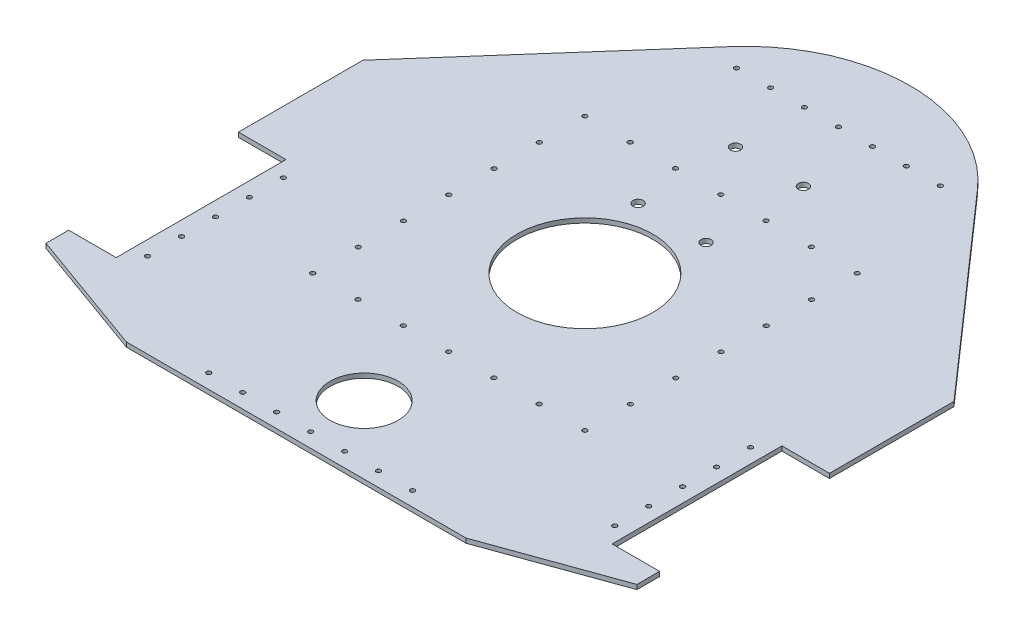
SolidWorks part; units mm, degrees
ref_plane "Front Plane" through (0, 0, 0) normal (0, 0, 1) x (1, 0, 0)
ref_plane "Top Plane" through (0, 0, 0) normal (0, 1, 0) x (1, 0, 0)
ref_plane "Right Plane" through (0, 0, 0) normal (1, 0, 0) x (0, 0, -1)
sketch "Sketch1" plane through (0, 0, 0) normal (0, 1, 0) x (1, 0, 0)
  line L0 (-240, -25) -> (240, -25) construction
  line L1 (240, -25) -> (0, 215) construction
  line L2 (0, 215) -> (-240, -25) construction
  line L3 (0, 215) -> (0, -25) construction
  line L6 (-219, 50) -> (-219, -100)
  line L7 (-219, -100) -> (-261, -100)
  line L8 (-261, -100) -> (-261, -120)
  line L10 (-150, -160) -> (150, -160)
  line L11 (-219, 50) -> (-261, 50)
  line L12 (-261, 50) -> (-261, 160)
  line L13 (-261, 160) -> (-110, 331.6587)
  line L14 (-150, -160) -> (-261, -120)
  line L15 (261, 160) -> (110, 331.6587)
  line L16 (150, -160) -> (261, -120)
  line L18 (261, -100) -> (261, -120)
  line L19 (219, -100) -> (261, -100)
  line L20 (219, 50) -> (219, -100)
  line L21 (219, 50) -> (261, 50)
  line L22 (261, 50) -> (261, 160)
  arc A7 (110, 331.6587) -> (-110, 331.6587) centre (0, 237.0979) ccw
  circle A8 centre (0, 64.773) radius 330 construction
  point P11 (-567.7272, -8.2112)
  point P29 (0, 331.6587)
  dimension "D1" = 480
  dimension "D4" = 75
  dimension "D6" = 20
  dimension "D7" = 42
  dimension "D2" = 240
  dimension "D3" = 21
  dimension "D5" = 75
  dimension "D8" = 20
  dimension "D9" = 21
  dimension "D10" = 21
  dimension "D11" = 110
  dimension "D12" = 110
  dimension "D13" = 150
  dimension "D14" = 42
  dimension "D15" = 300
extrude "Boss-Extrude1" add sketch "Sketch1" along normal blind 4
sketch "Sketch2" plane through (0, 4, 0) normal (0, 1, 0) x (1, 0, 0)
  line L0 (-206.3, 24.3269) -> (-206.3, -74.3269) construction
  line L1 (-219, 50) -> (-219, -100) construction
  line L2 (0, 319.1541) -> (0, -121.9152) construction
  line L4 (-219, 50) -> (-261, 50) construction
  line L5 (219, 50) -> (261, 50) construction
  circle A0 centre (-206.3, -25) radius 2
  circle A1 centre (-206.3, 5) radius 2
  circle A2 centre (-206.3, 35) radius 2
  circle A3 centre (-206.3, -55) radius 2
  circle A4 centre (-206.3, -85) radius 2
  circle A6 centre (206.3, -85) radius 2
  circle A7 centre (206.3, -55) radius 2
  circle A8 centre (206.3, -25) radius 2
  circle A9 centre (206.3, 5) radius 2
  circle A10 centre (206.3, 35) radius 2
  dimension "D2" = 3
  dimension "D1" = 12.7
  dimension "D4" = 75
  dimension "D5" = 75
  dimension "D6" = 12.7
  dimension "D3" = 3
extrude "Cut-Extrude1" cut sketch "Sketch2" against normal up to surface (4 mm away) up to face at (0, 0, -17.1134)
sketch "Sketch4" plane through (0, 4, 0) normal (0, 1, 0) x (1, 0, 0)
  line L0 (0, 0) -> (0, -135) construction
  line L1 (-120.2082, 215.2082) -> (-120.2082, -25.2082) construction
  line L2 (-219, -25) -> (219, -25) construction
  line L7 (-219, 50) -> (-219, -100) construction
  line L8 (219, 50) -> (219, -100) construction
  line L9 (-150, -160) -> (150, -160) construction
  line L10 (0, 382.1556) -> (0, -160) construction
  line L11 (0, 95) -> (-120.2082, 215.2082) construction
  circle A5 centre (0, -100) radius 30
  arc A6 (110, 331.6587) -> (-110, 331.6587) centre (0, 237.0979) ccw construction
  circle A7 centre (-120.2082, 215.2082) radius 2
  circle A8 centre (0, 95) radius 60
  circle A9 centre (120.2082, 215.2082) radius 2
  circle A10 centre (120.2082, -25.2082) radius 2
  circle A11 centre (-120.2082, -25.2082) radius 2
  circle A12 centre (-120.2082, 95) radius 2
  circle A13 centre (-120.2082, 135) radius 2
  circle A14 centre (-120.2082, 175) radius 2
  circle A15 centre (-120.2082, 55) radius 2
  circle A16 centre (-120.2082, 15) radius 2
  circle A17 centre (120.2082, 15) radius 2
  circle A18 centre (120.2082, 55) radius 2
  circle A19 centre (120.2082, 95) radius 2
  circle A20 centre (120.2082, 135) radius 2
  circle A21 centre (120.2082, 175) radius 2
  circle A22 centre (-80.2082, 215.2082) radius 2
  circle A23 centre (-80.2082, -25.2082) radius 2
  circle A24 centre (-40.2082, 215.2082) radius 2
  circle A25 centre (-40.2082, -25.2082) radius 2
  circle A26 centre (-0.2082, 215.2082) radius 2
  circle A27 centre (-0.2082, -25.2082) radius 2
  circle A28 centre (39.7918, 215.2082) radius 2
  circle A29 centre (39.7918, -25.2082) radius 2
  circle A30 centre (79.7918, 215.2082) radius 2
  circle A31 centre (79.7918, -25.2082) radius 2
  point P31 (0, 95)
  dimension "D1" = 120
  dimension "D4" = 60
  dimension "D7" = 3
  dimension "D3" = 45
  dimension "D5" = 60
  dimension "D2" = 170
  dimension "D8" = 3
  dimension "D9" = 6
  dimension "D6" = 4
extrude "Cut-Extrude2" cut sketch "Sketch4" against normal up to surface (4 mm away) up to face at (-206.3, 0, -3)
sketch "Sketch5" plane through (0, 4, 0) normal (0, 1, 0) x (1, 0, 0)
  line L0 (-219, -25) -> (219, -25) construction
  line L1 (-219, 50) -> (-219, -100) construction
  line L2 (219, 50) -> (219, -100) construction
  line L3 (0, 0) -> (0, 215) construction
  circle A0 centre (-30, 172) radius 4.5
  circle A1 centre (30, 172) radius 4.5
  circle A2 centre (30, 258) radius 4.5
  circle A3 centre (-30, 258) radius 4.5
  dimension "D2" = 30
  dimension "D1" = 215
  dimension "D3" = 43
  dimension "D4" = 2
  dimension "D5" = 2
extrude "Cut-Extrude3" cut sketch "Sketch5" against normal up to surface (4 mm away) up to face at (-80.2082, 0, -213.2082)
sketch "Sketch6" plane through (0, 4, 0) normal (0, 1, 0) x (1, 0, 0)
  line L0 (-110, 331.6587) -> (110, 331.6587) construction
  line L1 (0, 331.6587) -> (0, 301.6408) construction
  line L2 (0, -135) -> (0, -101.3263) construction
  line L4 (-150, -160) -> (150, -160) construction
  circle A0 centre (0, 318.9587) radius 2
  circle A1 centre (30, 318.9587) radius 2
  circle A2 centre (60, 318.9587) radius 2
  circle A3 centre (90, 318.9587) radius 2
  circle A4 centre (-30, 318.9587) radius 2
  circle A5 centre (-60, 318.9587) radius 2
  circle A6 centre (-90, 318.9587) radius 2
  circle A7 centre (0, -147.3) radius 2
  circle A8 centre (30, -147.3) radius 2
  circle A9 centre (60, -147.3) radius 2
  circle A10 centre (90, -147.3) radius 2
  circle A11 centre (-30, -147.3) radius 2
  circle A12 centre (-60, -147.3) radius 2
  circle A13 centre (-90, -147.3) radius 2
  dimension "D1" = 12.7
  dimension "D4" = 12.7
  dimension "D2" = 4
  dimension "D3" = 4
  dimension "D5" = 4
  dimension "D6" = 4
extrude "Cut-Extrude4" cut sketch "Sketch6" against normal up to surface (4 mm away) up to face at (-30, 0, -253.5)
